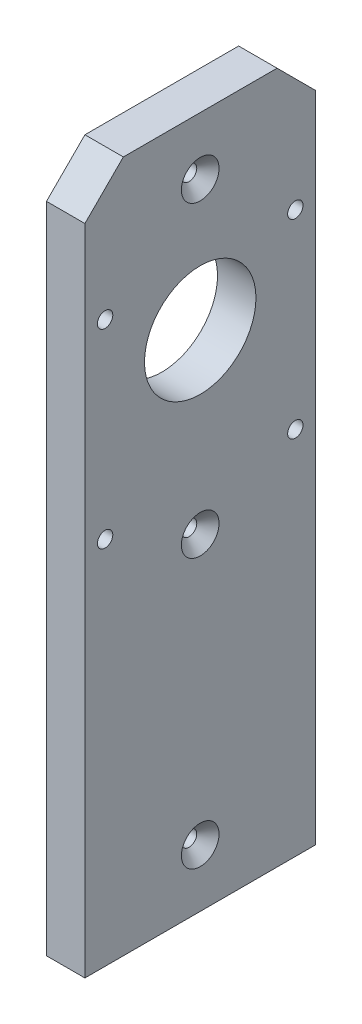
SolidWorks part; units mm, degrees
ref_plane "Спереди" through (0, 0, 0) normal (0, 0, 1) x (1, 0, 0)
ref_plane "Сверху" through (0, 0, 0) normal (0, 1, 0) x (1, 0, 0)
ref_plane "Справа" through (0, 0, 0) normal (1, 0, 0) x (0, 0, -1)
sketch "Эскиз1" plane through (0, 0, 0) normal (1, 0, 0) x (0, 0, -1)
  line L0 (4.0964, -129.9375) -> (4.0964, 50.0625) construction
  line L1 (-25.9036, 50.0625) -> (34.0964, 50.0625)
  line L2 (-25.9036, 50.0625) -> (-25.9036, -129.9375)
  line L3 (-25.9036, -129.9375) -> (34.0964, -129.9375)
  line L4 (34.0964, 50.0625) -> (34.0964, -129.9375)
  dimension "D1" = 60
  dimension "D2" = 180
extrude "Бобышка-Вытянуть1" add sketch "Эскиз1" along normal blind 10
sketch "Эскиз2" plane through (0, 0, 0) normal (-1, 0, 0) x (0, 0, 1)
  circle A0 centre (-4.0964, 1.0625) radius 14.5
  dimension "D1" = 29
extrude "Вырез-Вытянуть1" cut sketch "Эскиз2" against normal blind 30
sketch "Эскиз3" plane through (0, 0, 0) normal (-1, 0, 0) x (0, 0, 1)
  circle A0 centre (-28.8451, 15.8112) radius 2
  circle A1 centre (-28.8451, -33.6863) radius 2
  circle A2 centre (20.6524, 15.8112) radius 2
  circle A3 centre (20.6524, -33.6863) radius 2
  dimension "D1" = 4
  dimension "D2" = 4
  dimension "D3" = 4
  dimension "D4" = 4
extrude "Вырез-Вытянуть2" cut sketch "Эскиз3" against normal blind 10
chamfer "Фаска2" distance 2 angle 45 4 edges at (0, 15.8112, 22.6524) (0, -33.6863, 22.6524) (0, -33.6863, -26.8451) (0, 15.8112, -26.8451)
sketch "Эскиз4" plane through (10, 0, 0) normal (1, 0, 0) x (0, 0, -1)
  line L0 (4.0964, 50.0625) -> (4.0964, -129.9375) construction
  line L1 (34.0964, 50.0625) -> (-25.9036, 50.0625) construction
  line L2 (-25.9036, -129.9375) -> (34.0964, -129.9375) construction
  circle A0 centre (4.0964, -114.9375) radius 2
  circle A1 centre (4.0964, -44.9375) radius 2
  circle A2 centre (4.0964, 35.0625) radius 2
  dimension "D1" = 4
  dimension "D2" = 4
  dimension "D3" = 4
  dimension "D4" = 70
  dimension "D5" = 15
  dimension "D6" = 15
extrude "Вырез-Вытянуть3" cut sketch "Эскиз4" against normal blind 15
chamfer "Фаска3" distance 2.9 angle 45 3 edges at (10, 35.0625, -6.0964) (10, -44.9375, -6.0964) (10, -114.9375, -6.0964)
chamfer "Фаска4" distance 10 angle 45 2 edges at (5, 50.0625, -34.0964) (5, 50.0625, 25.9036)
sketch "Эскиз5" plane through (0, -129.9375, 0) normal (0, -1, 0) x (1, 0, 0)
  line L0 (5, 25.9036) -> (5, -34.0964) construction
  line L1 (10, 25.9036) -> (0, 25.9036) construction
  line L2 (10, -34.0964) -> (0, -34.0964) construction
  circle A0 centre (5, 19.9036) radius 1.65
  circle A1 centre (5, -28.0964) radius 1.65
  dimension "D1" = 3.3
  dimension "D2" = 3.3
  dimension "D3" = 6
  dimension "D4" = 6
extrude "Вырез-Вытянуть4" cut sketch "Эскиз5" against normal blind 15
